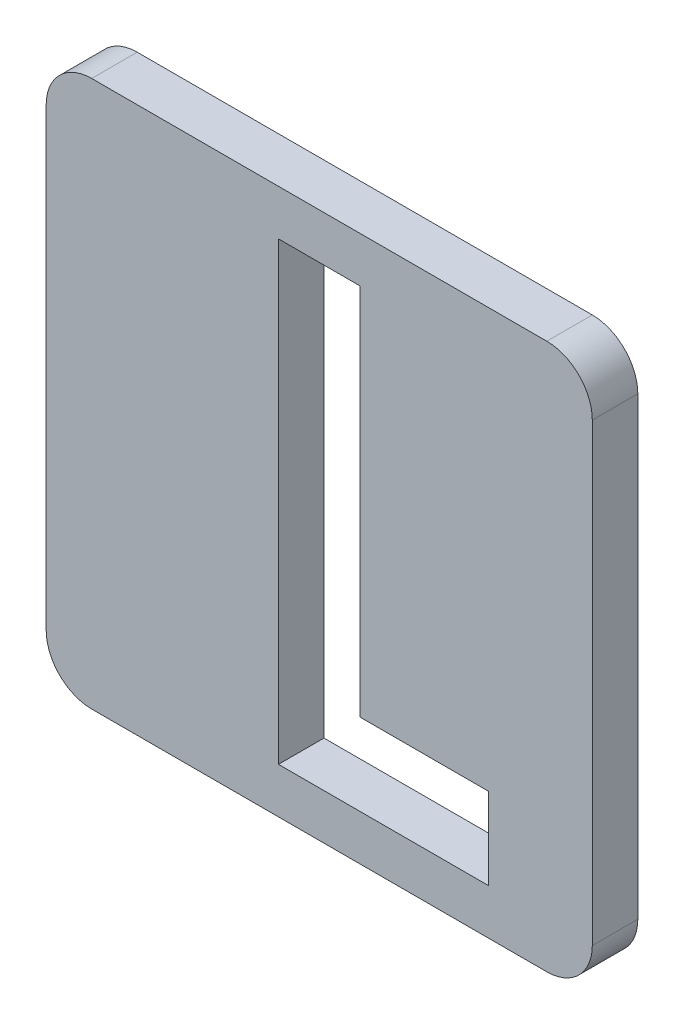
SolidWorks part; units mm, degrees
ref_plane "Front Plane" through (0, 0, 0) normal (0, 0, 1) x (1, 0, 0)
ref_plane "Top Plane" through (0, 0, 0) normal (0, 1, 0) x (1, 0, 0)
ref_plane "Right Plane" through (0, 0, 0) normal (1, 0, 0) x (0, 0, -1)
sketch "Sketch1" plane through (0, 0, 0) normal (0, 0, 1) x (1, 0, 0)
  line L1 (-50, 60) -> (50, 60)
  line L2 (-60, 50) -> (-60, -50)
  line L3 (-50, -60) -> (50, -60)
  line L4 (60, 50) -> (60, -50)
  line L5 (-60, 60) -> (60, -60) construction
  line L6 (-60, -60) -> (60, 60) construction
  arc A0 (-60, -50) -> (-50, -60) centre (-50, -50) ccw
  arc A1 (50, -60) -> (60, -50) centre (50, -50) ccw
  arc A2 (50, 60) -> (60, 50) centre (50, 50) cw
  arc A3 (-50, 60) -> (-60, 50) centre (-50, 50) ccw
  point P0 (0, 0)
  dimension "D3" = 10
  dimension "D1" = 120
  dimension "D2" = 120
extrude "Boss-Extrude1" add sketch "Sketch1" along normal blind 10 contours A3 L2 A0 L3 A1 L4 A2 L1
sketch "Sketch2" plane through (0, 0, 10) normal (0, 0, 1) x (1, 0, 0)
  line L0 (0, 0) -> (0, 40) construction
  line L1 (-50, 50) -> (50, 50) construction
  line L2 (-50, 50) -> (-50, -50) construction
  line L3 (-50, -50) -> (50, -50) construction
  line L4 (50, 50) -> (50, -50) construction
  line L5 (-50, 50) -> (50, -50) construction
  line L6 (-50, -50) -> (50, 50) construction
  line L7 (0, 40) -> (-40, 40) construction
  line L8 (-40, 40) -> (-40, 0) construction
  line L9 (-40, 0) -> (0, 0) construction
  line L11 (0, 20) -> (-20, 20) construction
  line L12 (-20, 40) -> (-20, 20) construction
  circle A0 centre (0, 40) radius 4 construction
  circle A1 centre (0, 20) radius 4 construction
  circle A2 centre (0, 0) radius 4 construction
  circle A3 centre (-20, 20) radius 4 construction
  circle A4 centre (-20, 40) radius 4 construction
  circle A5 centre (-40, 40) radius 4 construction
  circle A6 centre (0, 0) radius 4 construction
  circle A7 centre (20, 0) radius 4 construction
  circle A8 centre (40, 0) radius 4 construction
  circle A9 centre (40, 20) radius 4 construction
  circle A10 centre (40, 40) radius 4 construction
  circle A11 centre (20, 20) radius 4 construction
  circle A12 centre (0, 0) radius 4 construction
  circle A13 centre (0, -20) radius 4 construction
  circle A14 centre (0, -40) radius 4 construction
  circle A15 centre (20, -40) radius 4 construction
  circle A16 centre (40, -40) radius 4 construction
  circle A17 centre (20, -20) radius 4 construction
  circle A18 centre (0, 0) radius 4 construction
  circle A19 centre (-20, 0) radius 4 construction
  circle A20 centre (-40, 0) radius 4 construction
  circle A21 centre (-40, -20) radius 4 construction
  circle A22 centre (-40, -40) radius 4 construction
  circle A23 centre (-20, -20) radius 4 construction
  text T0 "L" font "Century Gothic" height 100
  point P0 (0, 0)
  point P55 (0, 0)
  dimension "D4" = 8
  dimension "D1" = 100
  dimension "D2" = 100
  dimension "D3" = 40
  dimension "D5" = 4
extrude "Cut-Extrude25" cut sketch "Sketch2" against normal blind 10
